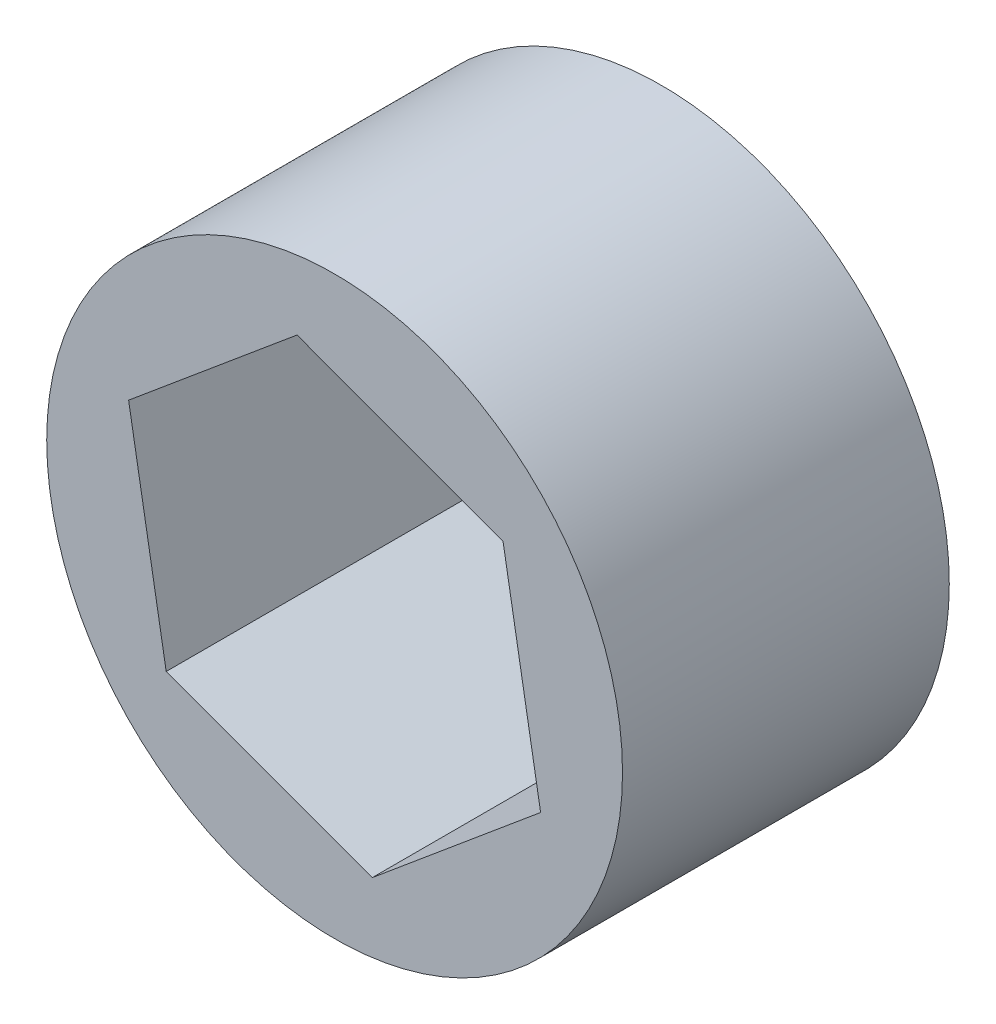
SolidWorks part; units mm, degrees
ref_plane "Front Plane" through (0, 0, 0) normal (0, 0, 1) x (1, 0, 0)
ref_plane "Top Plane" through (0, 0, 0) normal (0, 1, 0) x (1, 0, 0)
ref_plane "Right Plane" through (0, 0, 0) normal (1, 0, 0) x (0, 0, -1)
sketch "Sketch1" plane through (0, 0, 0) normal (0, 0, 1) x (1, 0, 0)
  line L1 (-7.1552, 2.6236) -> (-5.8497, -4.8848)
  line L2 (-5.8497, -4.8848) -> (1.3055, -7.5084)
  line L3 (1.3055, -7.5084) -> (7.1552, -2.6236)
  line L4 (7.1552, -2.6236) -> (5.8497, 4.8848)
  line L5 (5.8497, 4.8848) -> (-1.3055, 7.5084)
  line L6 (-1.3055, 7.5084) -> (-7.1552, 2.6236)
  circle A0 centre (0, 0) radius 10
  circle A1 centre (0, 0) radius 6.6 construction
  dimension "D1" = 13.2
  dimension "D2" = 20
extrude "Boss-Extrude1" add sketch "Sketch1" along normal blind 11.35
